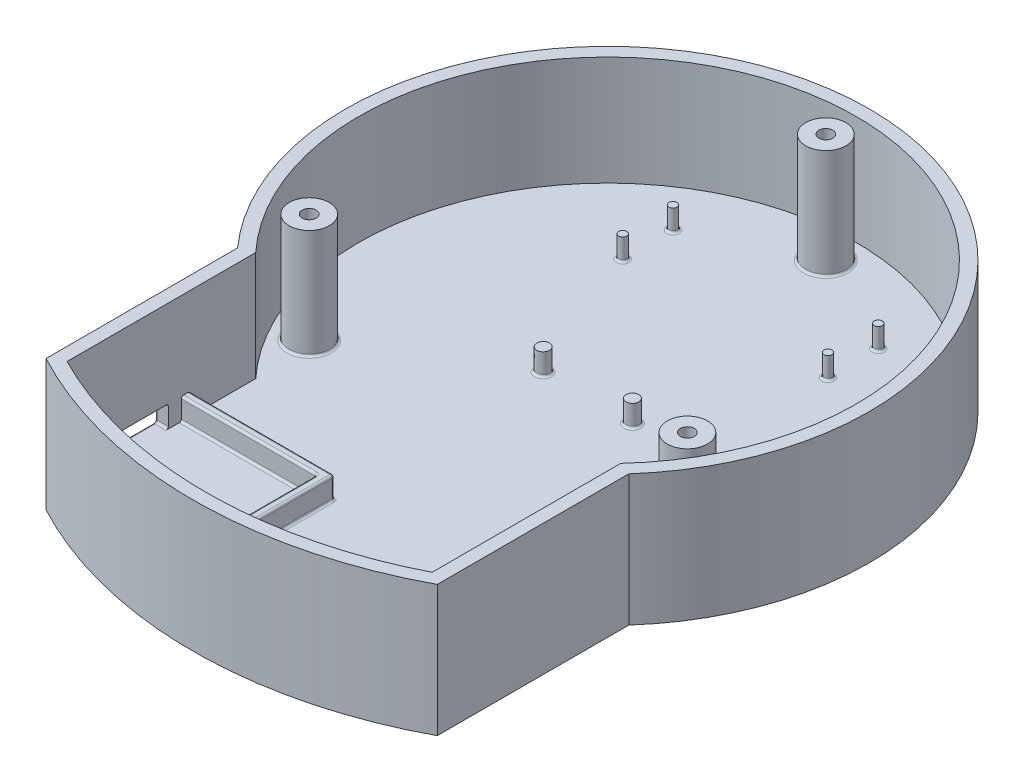
SolidWorks part; units mm, degrees
ref_plane "Alzado" through (0, 0, 0) normal (0, 0, 1) x (1, 0, 0)
ref_plane "Planta" through (0, 0, 0) normal (0, 1, 0) x (1, 0, 0)
ref_plane "Vista lateral" through (0, 0, 0) normal (1, 0, 0) x (0, 0, -1)
sketch "Croquis1" plane through (0, 0, 0) normal (0, 1, 0) x (1, 0, 0)
  line L0 (0, 0) -> (0, 50) construction
  circle A1 centre (0, 0) radius 60
  circle A2 centre (0, 50) radius 1.6
  circle A3 centre (43.3013, -25) radius 1.6
  circle A4 centre (-43.3013, -25) radius 1.6
  point P11 (0, 0)
  dimension "D2" = 120
  dimension "D3" = 3.2
  dimension "D1" = 50
  dimension "D4" = 3
extrude "Saliente-Extruir1" add sketch "Croquis1" along normal blind 5
sketch "Croquis2" plane through (0, 5, 0) normal (0, 1, 0) x (1, 0, 0)
  line L0 (-44.8013, -24.4432) -> (-44.8013, -39.9105) construction
  line L1 (-44.8013, -24.4432) -> (44.8013, -24.4432) construction
  line L2 (-44.8013, -39.9105) -> (-44.8013, -83.7726)
  line L4 (44.8013, -39.9105) -> (44.8013, -83.7726)
  line L5 (44.8013, -24.4432) -> (44.8013, -39.9105) construction
  circle A0 centre (-43.3013, -25) radius 1.6 construction
  circle A1 centre (43.3013, -25) radius 1.6 construction
  arc A2 (-44.8013, -83.7726) -> (44.8013, -83.7726) centre (0, 0) ccw
  arc A3 (-44.8013, -39.9105) -> (44.8013, -39.9105) centre (0, 0) ccw
  circle A4 centre (0, 0) radius 60 construction
  dimension "D2" = 95
  dimension "D1" = 89.6025
extrude "Saliente-Extruir2" add sketch "Croquis2" against normal blind 5
sketch "Croquis3" plane through (0, 5, 0) normal (0, 1, 0) x (1, 0, 0)
  line L0 (-41.8013, -38.7512) -> (-41.8013, -81.9552)
  line L1 (41.8013, -81.9552) -> (41.8013, -38.7512)
  line L2 (-44.8013, -39.9105) -> (-44.8013, -83.7726)
  line L3 (44.8013, -83.7726) -> (44.8013, -39.9105)
  line L4 (-44.8013, -39.9105) -> (-44.8013, -83.7726)
  line L5 (44.8013, -83.7726) -> (44.8013, -39.9105)
  arc A0 (41.8013, -38.7512) -> (-41.8013, -38.7512) centre (0, 0) ccw
  arc A1 (-41.8013, -81.9552) -> (41.8013, -81.9552) centre (0, 0) ccw
  arc A2 (44.8013, -39.9105) -> (-44.8013, -39.9105) centre (0, 0) ccw
  arc A3 (-44.8013, -83.7726) -> (44.8013, -83.7726) centre (0, 0) ccw
  arc A4 (44.8013, -39.9105) -> (-44.8013, -39.9105) centre (0, 0) ccw
  arc A5 (-44.8013, -83.7726) -> (44.8013, -83.7726) centre (0, 0) ccw
  dimension "D1" = 0
  dimension "D2" = 3
extrude "Saliente-Extruir3" add sketch "Croquis3" along normal blind 25
sketch "Croquis4" plane through (0, 5, 0) normal (0, 1, 0) x (1, 0, 0)
  line L0 (0, 0) -> (0, -4.5) construction
  line L1 (0, -4.5) -> (-10.225, -4.5) construction
  circle A0 centre (-10.225, -4.5) radius 1.45
  circle A1 centre (10.225, -4.5) radius 1.45
  dimension "D1" = 2.9
  dimension "D2" = 4.5
  dimension "D3" = 10.225
extrude "Saliente-Extruir4" add sketch "Croquis4" along normal blind 5
sketch "Croquis5" plane through (0, 5, 0) normal (0, 1, 0) x (1, 0, 0)
  line L0 (-23.5, 38.5) -> (-23.5, 27) construction
  line L1 (-23.5, 38.5) -> (23.5, 38.5) construction
  line L2 (-23.5, 27) -> (23.5, 27) construction
  line L3 (23.5, 38.5) -> (23.5, 27) construction
  line L4 (0, 0) -> (0, 27) construction
  circle A0 centre (23.5, 38.5) radius 0.925
  circle A1 centre (23.5, 27) radius 0.925
  circle A2 centre (-23.5, 27) radius 0.925
  circle A3 centre (-23.5, 38.5) radius 0.925
  point P14 (0, 27)
  dimension "D1" = 1.85
  dimension "D2" = 47
  dimension "D3" = 11.5
  dimension "D4" = 27
extrude "Saliente-Extruir5" add sketch "Croquis5" along normal blind 5
sketch "Croquis6" plane through (0, 5, 0) normal (0, 1, 0) x (1, 0, 0)
  circle A0 centre (0, 50) radius 1.6
  circle A1 centre (43.3013, -25) radius 1.6
  circle A2 centre (-43.3013, -25) radius 1.6
  circle A3 centre (0, 50) radius 4.6
  circle A4 centre (43.3013, -25) radius 4.6
  circle A5 centre (-43.3013, -25) radius 4.6
  dimension "D1" = 3
extrude "Saliente-Extruir6" add sketch "Croquis6" along normal blind 25
fillet "Redondeo1" radius 0.5 9 edges at (23.5, 5, -37.575) (23.5, 5, -26.075) (10.225, 5, 3.05) (-10.225, 5, 5.95) (-23.5, 5, -37.575) (-23.5, 5, -26.075) (43.3013, 5, 29.6) (0, 5, -45.4) (-43.3013, 5, 29.6)
sketch "Croquis7" plane through (-44.8013, 0, 0) normal (-1, 0, 0) x (0, 0, 1)
  line L0 (39.9105, 0) -> (83.7726, 0) construction
  line L1 (58.7726, 5) -> (73.7726, 5)
  line L2 (58.7726, 5) -> (58.7726, 10)
  line L3 (58.7726, 10) -> (73.7726, 10)
  line L4 (73.7726, 5) -> (73.7726, 10)
  line L5 (83.7726, 0) -> (83.7726, 30) construction
  dimension "D1" = 5
  dimension "D2" = 15
  dimension "D3" = 5
  dimension "D4" = 10
extrude "Cortar-Extruir1" cut sketch "Croquis7" against normal blind 5
fillet "Redondeo2" radius 0.5 8 edges at (-44.8013, 10, 66.2726) (-44.8013, 5, 66.2726) (-43.3013, 5, 73.7726) (-43.3013, 5, 58.7726) (-43.3013, 10, 73.7726) (-44.8013, 7.5, 73.7726) (-43.3013, 10, 58.7726) (-44.8013, 7.5, 58.7726)
sketch "Croquis9" plane through (0, 5, 0) normal (0, 1, 0) x (1, 0, 0)
  line L0 (-41.8013, -55.7726) -> (-10.8013, -55.7726)
  line L1 (-41.8013, -38.7512) -> (-41.8013, -59.2726) construction
  line L2 (-10.8013, -55.7726) -> (-10.8013, -76.7726)
  line L3 (-10.8013, -76.7726) -> (-41.8013, -76.7726)
  line L4 (-41.8013, -73.2726) -> (-41.8013, -81.9552) construction
  line L5 (-41.8013, -53.7726) -> (-41.8013, -55.7726)
  line L6 (-41.8013, -53.7726) -> (-8.8013, -53.7726)
  line L7 (-8.8013, -53.7726) -> (-8.8013, -78.7726)
  line L8 (-8.8013, -78.7726) -> (-41.8013, -78.7726)
  line L9 (-10.8013, -66.2726) -> (-41.8013, -66.2726) construction
  line L10 (-41.8013, -59.2726) -> (-41.8013, -73.2726) construction
  line L11 (-41.8013, -76.7726) -> (-41.8013, -78.7726)
  point P17 (-41.8013, -66.2726)
  dimension "D1" = 21
  dimension "D2" = 31
  dimension "D3" = 2
extrude "Saliente-Extruir7" add sketch "Croquis9" along normal blind 5
fillet "Redondeo3" radius 0.5 16 edges at (-25.3013, 5, 78.7726) (-25.3013, 10, 78.7726) (-25.3013, 5, 53.7726) (-25.3013, 10, 53.7726) (-8.8013, 5, 66.2726) (-8.8013, 10, 66.2726) (-10.8013, 7.5, 55.7726) (-26.3013, 5, 55.7726) (-26.3013, 10, 55.7726) (-10.8013, 5, 66.2726) (-10.8013, 10, 66.2726) (-26.3013, 5, 76.7726) (-26.3013, 10, 76.7726) (-10.8013, 7.5, 76.7726) (-8.8013, 7.5, 53.7726) (-8.8013, 7.5, 78.7726)
